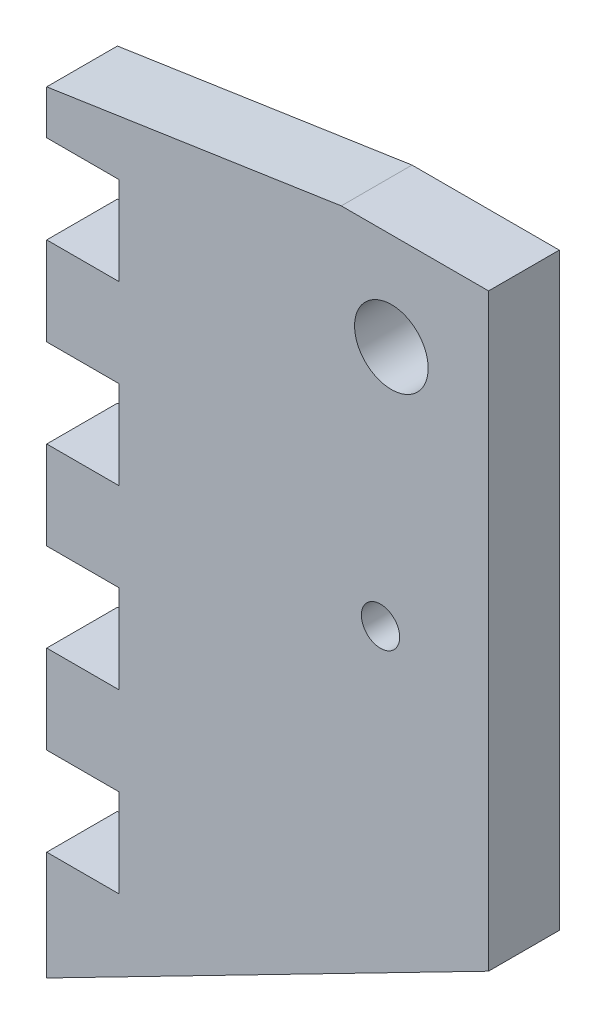
SolidWorks part; units mm, degrees
material "Thornel VCB-20 Carbon Cloth"
ref_plane "Front Plane" through (0, 0, 0) normal (0, 0, 1) x (1, 0, 0)
ref_plane "Top Plane" through (0, 0, 0) normal (0, 1, 0) x (1, 0, 0)
ref_plane "Right Plane" through (0, 0, 0) normal (1, 0, 0) x (0, 0, -1)
sketch "Sketch1" plane through (0, 0, 0) normal (0, 0, 1) x (1, 0, 0)
  line L0 (0, 0) -> (-38.1, 0)
  line L1 (0, 0) -> (0, -50.8)
  line L2 (-38.1, 0) -> (-38.1, -7.62)
  line L3 (-38.1, -7.62) -> (-31.877, -7.62)
  line L4 (-31.877, -7.62) -> (-31.877, -15.24)
  line L5 (-31.877, -15.24) -> (-38.1, -15.24)
  line L6 (-38.1, -45.72) -> (-38.1, -70.358)
  line L7 (-38.1, -15.24) -> (-38.1, -22.86)
  line L8 (-38.1, -22.86) -> (-31.877, -22.86)
  line L9 (-31.877, -22.86) -> (-31.877, -30.48)
  line L10 (-31.877, -30.48) -> (-38.1, -30.48)
  line L11 (-38.1, -30.48) -> (-38.1, -38.1)
  line L12 (-38.1, -38.1) -> (-31.877, -38.1)
  line L13 (-31.877, -38.1) -> (-31.877, -45.72)
  line L14 (-31.877, -45.72) -> (-38.1, -45.72)
  line L15 (-38.1, -70.358) -> (0, -50.8)
  circle A0 centre (-8.382, -8.382) radius 3.175
  dimension "D9" = 6.35
  dimension "D1" = 38.1
  dimension "D2" = 50.8
  dimension "D3" = 7.62
  dimension "D4" = 7.62
  dimension "D6" = 6.223
  dimension "D8" = 70.358
  dimension "D12" = 8.382
  dimension "D13" = 8.382
  dimension "D7" = 3
extrude "Boss-Extrude1" add sketch "Sketch1" along normal blind 6.096
sketch "Sketch2" plane through (0, 0, 0) normal (0, 0, -1) x (-1, 0, 0)
  line L5 (38.1, 0) -> (12.7, 0)
  line L6 (0, 0) -> (38.1, 0) construction
  line L7 (12.7, 0) -> (38.1, -3.81)
  line L8 (38.1, 0) -> (38.1, -7.62) construction
  line L9 (38.1, -3.81) -> (38.1, 0)
  dimension "D1" = 25.4
  dimension "D2" = 3.81
extrude "Cut-Extrude1" cut sketch "Sketch2" against normal blind 8.636
sketch "Sketch4" plane through (0, 0, 6.096) normal (0, 0, 1) x (1, 0, 0)
  line L0 (-38.1, -45.72) -> (-38.1, -53.34)
  line L1 (-38.1, -45.72) -> (-38.1, -70.358) construction
  line L2 (-38.1, -53.34) -> (-31.877, -53.34)
  line L3 (-31.877, -53.34) -> (-31.877, -60.96)
  line L4 (-31.877, -60.96) -> (-38.1, -60.96)
  line L5 (-38.1, -60.96) -> (-38.1, -53.34)
  line M18 (-38.1, -45.72) -> (-38.1, -70.358)
  dimension "D1" = 7.62
  dimension "D2" = 6.223
  dimension "D4" = 7.62
extrude "Cut-Extrude2" cut sketch "Sketch4" against normal through all contours L4 L3 L2 M18
sketch "Sketch5" plane through (0, 0, 0) normal (0, 0, -1) x (-1, 0, 0)
  line L0 (8.382, -8.382) -> (9.319, -29.6974) construction
  line L1 (8.382, -8.382) -> (8.382, -39.2411) construction
  circle A0 centre (8.382, -8.382) radius 3.175 construction
  circle A1 centre (9.319, -29.6974) radius 1.651
  dimension "D7" = 3.302
  dimension "D1" = 21.336
  dimension "D2" = 2.517
extrude "Cut-Extrude4" cut sketch "Sketch5" against normal up to surface (6.096 mm away) up to face at (-5.207, -8.382, 6.096)
ref_plane "Plane1" through (0, 0, 0) normal (0, 0, -1) x (-1, 0, 0)
